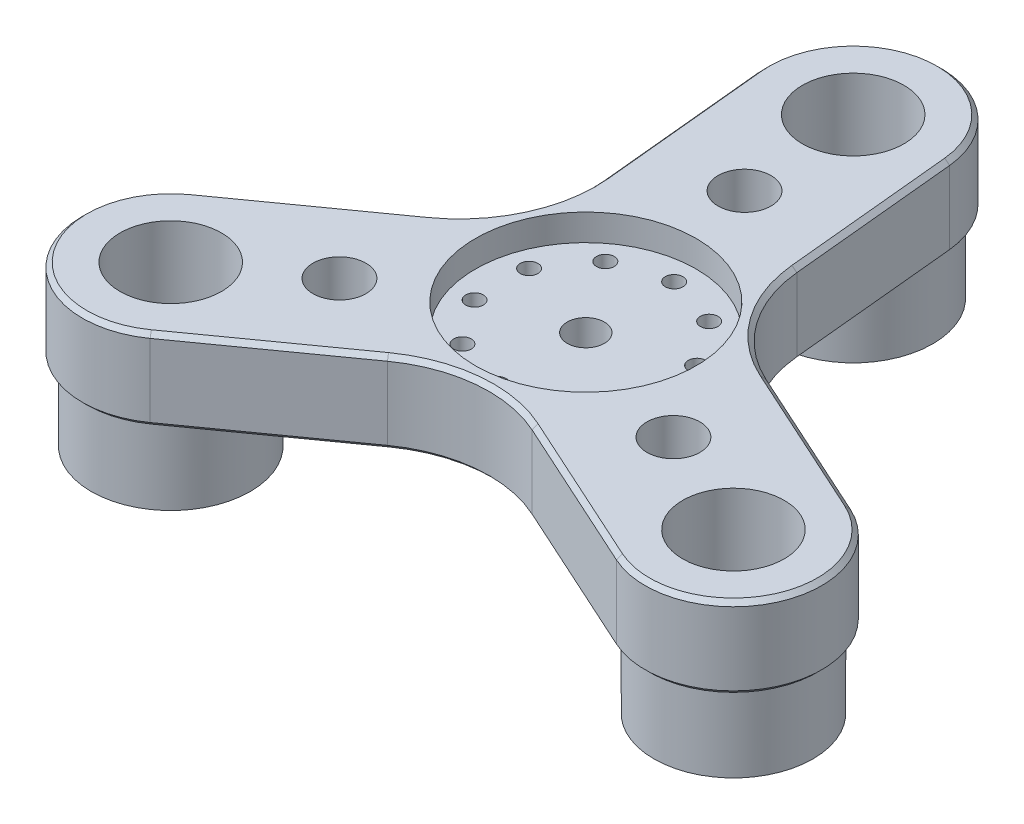
SolidWorks part; units mm, degrees
material "ﾒﾗﾐﾝ樹脂"
ref_plane "正面" through (0, 0, 0) normal (0, 0, 1) x (1, 0, 0)
ref_plane "平面" through (0, 0, 0) normal (0, 1, 0) x (1, 0, 0)
ref_plane "右側面" through (0, 0, 0) normal (1, 0, 0) x (0, 0, -1)
sketch "ｽｹｯﾁ1" plane through (0, 0, 0) normal (0, 1, 0) x (1, 0, 0)
  line L7 (-13.2076, 32.5732) -> (-10.5108, 4.7807)
  line L9 (-33.2315, -11.4509) -> (-10.5108, 4.7807)
  line L10 (-10.5108, 4.7807) -> (-10.5765, 5.0176)
  line L11 (34.813, -4.8485) -> (9.3957, 6.7123)
  line L12 (6.6989, 34.5048) -> (9.3957, 6.7123)
  line L13 (-21.6055, -27.7247) -> (1.1152, -11.493)
  line L14 (26.5326, -23.0538) -> (1.1152, -11.493)
  circle A1 centre (-27.4185, -19.5878) radius 10
  circle A2 centre (-3.2543, 33.539) radius 10
  circle A3 centre (30.6728, -13.9512) radius 10
  point P13 (0, 0)
  point P16 (0, 0)
  point P26 (0, 0)
  dimension "D1" = 3
  dimension "D2" = 58.3641
  dimension "D4" = 3
extrude "ﾎﾞｽ - 押し出し1" add sketch "ｽｹｯﾁ1" along normal blind 9.25 contours A2 | A3 L11 L12 A2 L7 L9 A1 L13 L14 | A3 | A1
sketch "ｽｹｯﾁ2" plane through (0, 9.25, 0) normal (0, 1, 0) x (1, 0, 0)
  circle A0 centre (-27.4185, -19.5878) radius 4.5
  circle A1 centre (-3.2543, 33.539) radius 4.5
  circle A2 centre (30.6728, -13.9512) radius 4.5
  point P9 (0, 0)
  dimension "D1" = 3
extrude "ｶｯﾄ - 押し出し1" cut sketch "ｽｹｯﾁ2" against normal up to next
sketch "ｽｹｯﾁ3" plane through (0, 0, 0) normal (0, -1, 0) x (1, 0, 0)
  circle A0 centre (-3.2543, -33.539) radius 9
  circle A1 centre (-27.4185, 19.5878) radius 9
  circle A2 centre (30.6728, 13.9512) radius 9
  point P9 (0, 0)
  dimension "D1" = 3
extrude "ﾎﾞｽ - 押し出し2" add sketch "ｽｹｯﾁ3" along normal blind 9.5
sketch "ｽｹｯﾁ4" plane through (0, 0, 0) normal (0, 1, 0) x (1, 0, 0)
  circle A0 centre (-3.2543, 33.539) radius 4.5
  circle A1 centre (30.6728, -13.9512) radius 4.5
  circle A2 centre (-27.4185, -19.5878) radius 4.5
  point P9 (0, 0)
  dimension "D1" = 3
extrude "ｶｯﾄ - 押し出し2" cut sketch "ｽｹｯﾁ4" against normal up to next
fillet "ﾌｨﾚｯﾄ1" radius 15 3 edges at (9.3957, 4.625, -6.7123) (1.1152, 4.625, 11.493) (-10.5108, 4.625, -4.7807)
sketch "ｽｹｯﾁ6" plane through (0, 9.25, 0) normal (0, 1, 0) x (1, 0, 0)
  circle A0 centre (0, 0) radius 12.5
extrude "ｶｯﾄ - 押し出し5" cut sketch "ｽｹｯﾁ6" against normal blind 3
chamfer "面取り1" distance 0.5 angle 45 12 edges at (-12.6231, 9.25, -5.7415) (-25.3945, 9.25, 5.8522) (-35.5554, 9.25, 25.4008) (-13.7685, 9.25, 22.126) (1.3393, 9.25, 13.8027) (17.7654, 9.25, 19.0662) (39.7755, 9.25, 18.0914) (26.0459, 9.25, 0.8609) (11.2838, 9.25, -8.0612) (7.6291, 9.25, -24.9184) (-4.2201, 9.25, -43.4923) (-12.2774, 9.25, -22.9869)
chamfer "面取り2" distance 0.5 angle 45 12 edges at (7.6291, 0, -24.9184) (11.2838, 0, -8.0612) (26.0459, 0, 0.8609) (39.7755, 0, 18.0914) (17.7654, 0, 19.0662) (1.3393, 0, 13.8027) (-13.7685, 0, 22.126) (-35.5554, 0, 25.4008) (-25.3945, 0, 5.8522) (-12.6231, 0, -5.7415) (-12.2774, 0, -22.9869) (-4.2201, 0, -43.4923)
sketch "ｽｹｯﾁ7" plane through (0, 0, 0) normal (0, -1, 0) x (1, 0, 0)
  circle A0 centre (0, 0) radius 4.71
extrude "ﾎﾞｽ - 押し出し3" add sketch "ｽｹｯﾁ7" along normal blind 2.5
sketch "ｽｹｯﾁ8" plane through (0, 6.25, 0) normal (0, 1, 0) x (1, 0, 0)
  circle A0 centre (0, 10) radius 1
  circle A1 centre (5.8779, 8.0902) radius 1
  circle A2 centre (9.5106, 3.0902) radius 1
  circle A3 centre (9.5106, -3.0902) radius 1
  circle A4 centre (5.8779, -8.0902) radius 1
  circle A5 centre (0, -10) radius 1
  circle A6 centre (-5.8779, -8.0902) radius 1
  circle A7 centre (-9.5106, -3.0902) radius 1
  circle A8 centre (-9.5106, 3.0902) radius 1
  circle A9 centre (-5.8779, 8.0902) radius 1
  point P24 (0, 0)
  dimension "D1" = 10
extrude "ｶｯﾄ - 押し出し6" cut sketch "ｽｹｯﾁ8" against normal up to next
sketch "ｽｹｯﾁ9" plane through (0, -2.5, 0) normal (0, -1, 0) x (1, 0, 0)
  circle A0 centre (0, 0) radius 2.1
extrude "ｶｯﾄ - 押し出し7" cut sketch "ｽｹｯﾁ9" against normal up to next
sketch "ｽｹｯﾁ10" plane through (0, 9.25, 0) normal (0, 1, 0) x (1, 0, 0)
  circle A0 centre (-1.9315, 19.9065) radius 3
  circle A1 centre (18.2053, -8.2805) radius 3
  circle A2 centre (-16.2738, -11.626) radius 3
  point P8 (0, 0)
  dimension "D1" = 3
extrude "ｶｯﾄ - 押し出し9" cut sketch "ｽｹｯﾁ10" against normal up to next
sketch "ｽｹｯﾁ11" plane through (0, 9.25, 0) normal (0, 1, 0) x (1, 0, 0)
  circle A0 centre (-3.2543, 33.539) radius 5.75
  circle A1 centre (30.6728, -13.9512) radius 5.75
  circle A2 centre (-27.4185, -19.5878) radius 5.75
  point P9 (0, 0)
  dimension "D1" = 3
extrude "ｶｯﾄ - 押し出し10" cut sketch "ｽｹｯﾁ11" against normal up to next
sketch "ｽｹｯﾁ12" plane through (0, -9.5, 0) normal (0, -1, 0) x (-1, 0, 0)
  circle A0 centre (3.2543, 33.539) radius 5.75
  circle A1 centre (3.2543, 33.539) radius 9
  circle A2 centre (27.4185, -19.5878) radius 9
  circle A3 centre (-30.6728, -13.9512) radius 9
  point P10 (0, 0)
  dimension "D1" = 3
extrude "ｶｯﾄ - 押し出し11" cut sketch "ｽｹｯﾁ12" against normal blind 0.75
